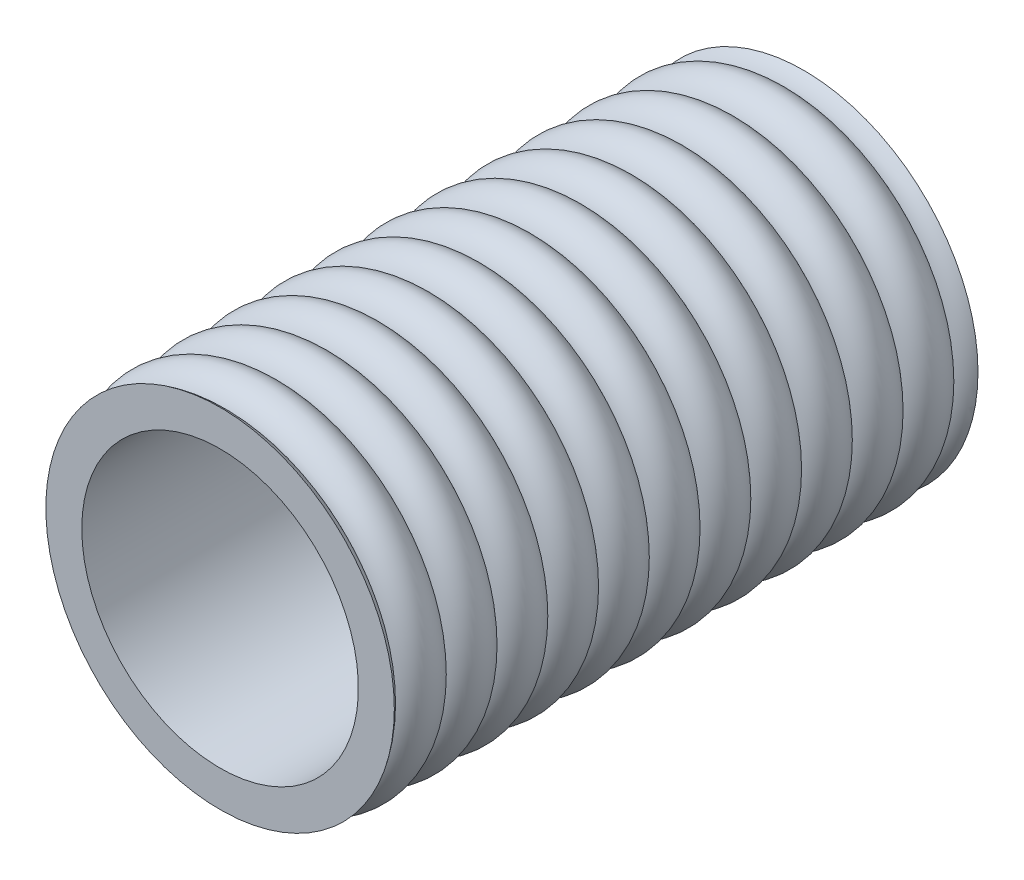
SolidWorks part; units mm, degrees
ref_plane "Front" through (0, 0, 0) normal (0, 0, 1) x (1, 0, 0)
ref_plane "Top" through (0, 0, 0) normal (0, 1, 0) x (1, 0, 0)
ref_plane "Right" through (0, 0, 0) normal (1, 0, 0) x (0, 0, -1)
sketch "Sketch1" plane through (0, 0, 0) normal (0, 0, 1) x (1, 0, 0)
  circle A0 centre (0, 0) radius 7
  dimension "D1" = 14
extrude "Boss-Extrude1" add sketch "Sketch1" along normal blind 23
sketch "Sketch2" plane through (0, 0, 23) normal (0, 0, 1) x (1, 0, 0)
  circle A0 centre (0, 0) radius 5.4
  dimension "D1" = 10.8
extrude "Cut-Extrude1" cut sketch "Sketch2" against normal blind 2
sketch "Sketch3" plane through (0, 0, 0) normal (0, 0, -1) x (-1, 0, 0)
  circle A0 centre (0, 0) radius 5.45
  dimension "D1" = 10.9
extrude "Cut-Extrude2" cut sketch "Sketch3" against normal through all
sketch "Sketch6" plane through (0, 0, 0) normal (0, 1, 0) x (1, 0, 0)
  line L0 (0, -23) -> (0, 0) construction
  line L1 (-7, -23) -> (7, -23) construction
  line L2 (7, -23) -> (7, 0) construction
  line L4 (6.866, -23) -> (7.6826, -23)
  line L5 (7.6826, -23) -> (7.6826, 0)
  line L6 (7.6826, 0) -> (6.866, 0)
  line L7 (7, 0) -> (-7, 0) construction
  arc A0 (6, -12.5) -> (6, -10.5) centre (6, -11.5) ccw
  arc A1 (6, -14.5) -> (6, -12.5) centre (6, -13.5) ccw
  arc A2 (6, -16.5) -> (6, -14.5) centre (6, -15.5) ccw
  arc A3 (6, -18.5) -> (6, -16.5) centre (6, -17.5) ccw
  arc A4 (6, -20.5) -> (6, -18.5) centre (6, -19.5) ccw
  arc A5 (6, -22.5) -> (6, -20.5) centre (6, -21.5) ccw
  arc A6 (6.866, -23) -> (6, -22.5) centre (6, -23.5) ccw
  arc A7 (6, -10.5) -> (6, -8.5) centre (6, -9.5) ccw
  arc A8 (6, -8.5) -> (6, -6.5) centre (6, -7.5) ccw
  arc A9 (6, -6.5) -> (6, -4.5) centre (6, -5.5) ccw
  arc A10 (6, -4.5) -> (6, -2.5) centre (6, -3.5) ccw
  arc A11 (6, -2.5) -> (6, -0.5) centre (6, -1.5) ccw
  arc A12 (6, -0.5) -> (6.866, 0) centre (6, 0.5) ccw
  dimension "D2" = 7
revolve "Cut-Revolve1" cut sketch "Sketch6" angle 360 about L0
